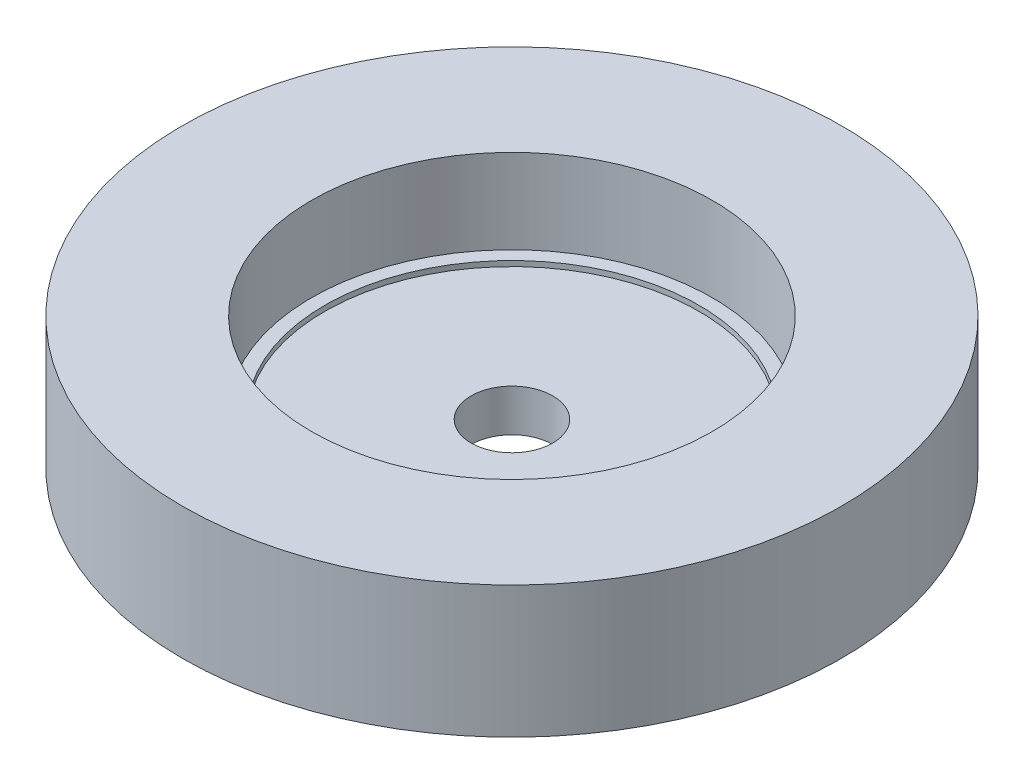
SolidWorks part; units mm, degrees
ref_plane "正面" through (0, 0, 0) normal (0, 0, 1) x (1, 0, 0)
ref_plane "平面" through (0, 0, 0) normal (0, 1, 0) x (1, 0, 0)
ref_plane "右側面" through (0, 0, 0) normal (1, 0, 0) x (0, 0, -1)
sketch "ｽｹｯﾁ1" plane through (0, 0, 0) normal (0, 1, 0) x (1, 0, 0)
  circle A0 centre (0, 0) radius 7.6
  circle A1 centre (0, 0) radius 12.5
  dimension "D1" = 15.2
  dimension "D2" = 25
extrude "ﾎﾞｽ - 押し出し1" add sketch "ｽｹｯﾁ1" along normal blind 5
sketch "ｽｹｯﾁ2" plane through (0, 0, 0) normal (0, -1, 0) x (1, 0, 0)
  circle A0 centre (0, 0) radius 7.6
  circle A1 centre (0, 0) radius 7.6 construction
  circle A2 centre (0, 0) radius 1.55
  dimension "D1" = 3.1
extrude "ﾎﾞｽ - 押し出し2" add sketch "ｽｹｯﾁ2" against normal blind 1.6
sketch "ｽｹｯﾁ3" plane through (0, 1.6, 0) normal (0, 1, 0) x (1, 0, 0)
  circle A0 centre (0, 0) radius 7.6
  circle A1 centre (0, 0) radius 7.1
  circle A2 centre (0, 0) radius 7.6 construction
  dimension "D1" = 0.5
extrude "ﾎﾞｽ - 押し出し3" add sketch "ｽｹｯﾁ3" along normal blind 0.2
